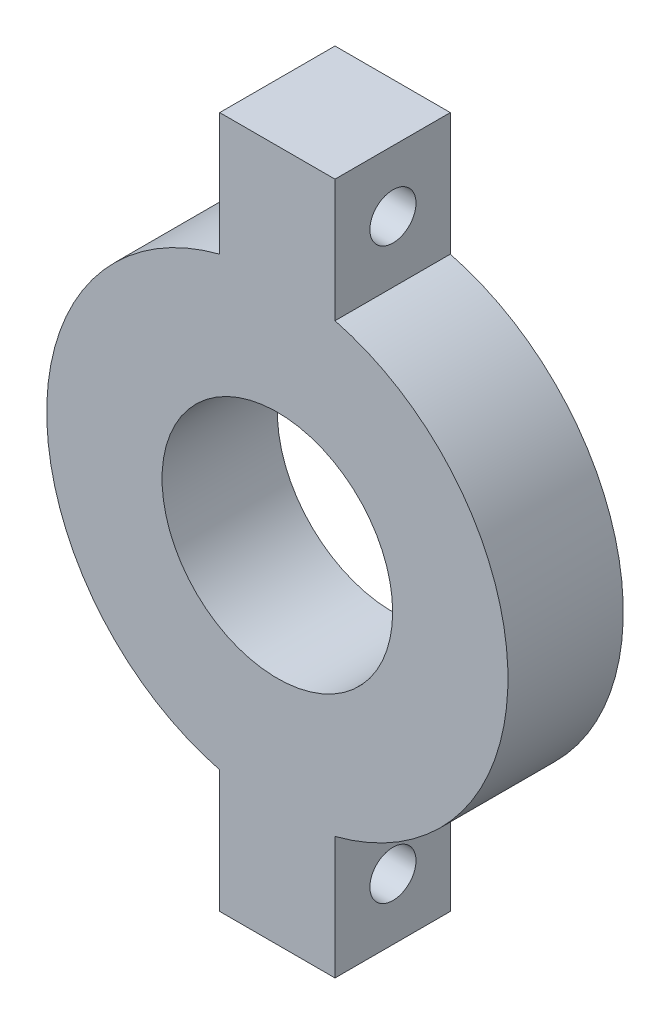
SolidWorks part; units mm, degrees
ref_plane "Plan de face" through (0, 0, 0) normal (0, 0, 1) x (1, 0, 0)
ref_plane "Plan de dessus" through (0, 0, 0) normal (0, 1, 0) x (1, 0, 0)
ref_plane "Plan de droite" through (0, 0, 0) normal (1, 0, 0) x (0, 0, -1)
sketch "Esquisse1" plane through (0, 0, 0) normal (0, 0, 1) x (1, 0, 0)
  circle A0 centre (0, 0) radius 5
  circle A1 centre (0, 0) radius 10
  dimension "D1" = 10
  dimension "D2" = 20
extrude "Boss.-Extru.1" add sketch "Esquisse1" along normal blind 5
sketch "Esquisse2" plane through (0, 0, 5) normal (0, 0, 1) x (1, 0, 0)
  line L12 (27.2852, 0) -> (-27.2852, 0) construction
  line L26 (0, 20.4609) -> (0, -20.4609) construction
  line L39 (2.5, 8) -> (-2.5, 8)
  line L40 (2.5, 8) -> (2.5, 15)
  line L41 (-2.5, 8) -> (-2.5, 15)
  line L42 (2.5, 15) -> (-2.5, 15)
  point P0 (0, 15)
  dimension "D1" = 5
  dimension "D2" = 7
  dimension "D3" = 8
extrude "Boss.-Extru.2" add sketch "Esquisse2" against normal blind 5
sketch "Esquisse3" plane through (-2.5, 0, 0) normal (-1, 0, 0) x (0, -1, 0)
  circle A0 centre (-12.3459, 2.4874) radius 1
  dimension "D1" = 2
extrude "Enlèv. mat.-Extru.1" cut sketch "Esquisse3" against normal blind 10
mirror "Symétrie1" about plane through (0, 0, 0) normal (0, 1, 0) of "Boss.-Extru.2", "Enlèv. mat.-Extru.1"
